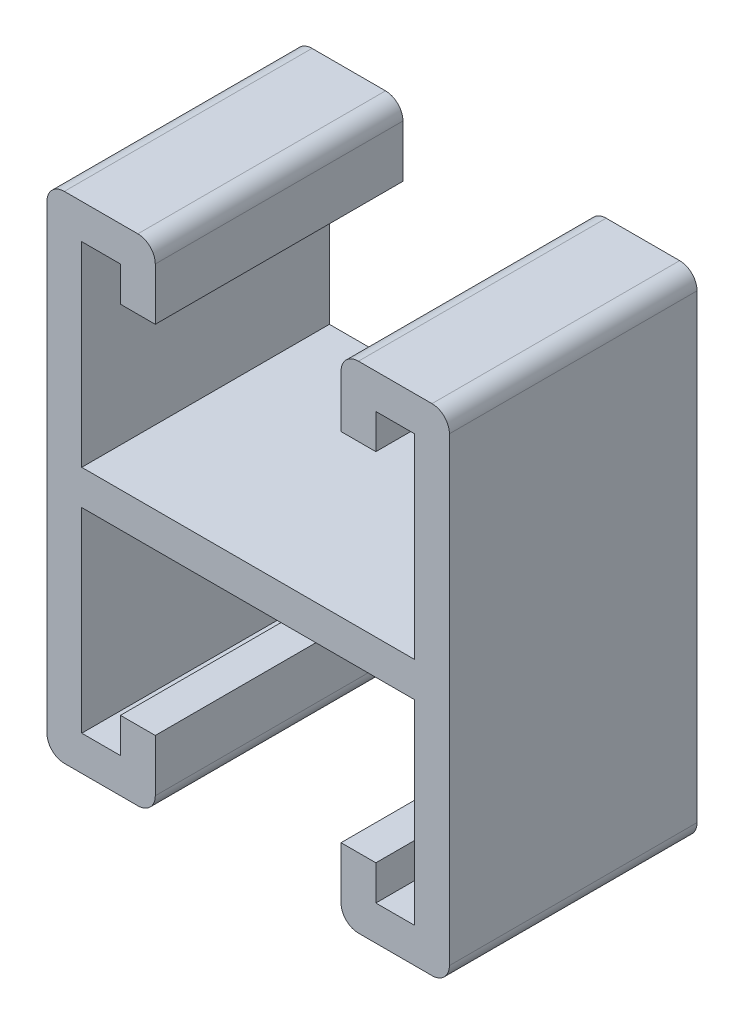
SolidWorks part; units mm, degrees
ref_plane "Plane1" through (0, 0, 0) normal (0, 0, 1) x (1, 0, 0)
ref_plane "Plane2" through (0, 0, 0) normal (0, 1, 0) x (1, 0, 0)
ref_plane "Plane3" through (0, 0, 0) normal (1, 0, 0) x (0, 0, -1)
sketch "Sketch1" plane through (0, 0, 0) normal (0, 0, 1) x (1, 0, 0)
  line L0 (-11.3109, 25.4) -> (-18.8516, 25.4)
  line L1 (-20.6375, 23.6141) -> (-20.6375, -23.6141)
  line L2 (25.727, 0) -> (-25.0678, 0) construction
  line L3 (20.6375, -23.6141) -> (20.6375, 23.6141)
  line L4 (18.8516, 25.4) -> (11.3109, 25.4)
  line L5 (9.525, 23.6141) -> (9.525, 18.2562)
  line L6 (-9.525, 23.6141) -> (-9.525, 18.2562)
  line L7 (-13.0969, 21.8281) -> (-13.0969, 18.2562)
  line L8 (-13.0969, 21.8281) -> (-17.0656, 21.8281)
  line L9 (-17.0656, 21.8281) -> (-17.0656, 1.7859)
  line L10 (-17.0656, 1.7859) -> (17.0656, 1.7859)
  line L11 (17.0656, 1.7859) -> (17.0656, 21.8281)
  line L12 (17.0656, 21.8281) -> (13.0969, 21.8281)
  line L13 (13.0969, 21.8281) -> (13.0969, 18.2562)
  line L14 (-13.0969, 18.2562) -> (-9.525, 18.2562)
  line L15 (9.525, 18.2562) -> (13.0969, 18.2562)
  line L16 (-11.3109, -25.4) -> (-18.8516, -25.4)
  line L17 (-13.0969, -21.8281) -> (-17.0656, -21.8281)
  line L18 (-13.0969, -21.8281) -> (-13.0969, -18.2562)
  line L19 (-9.525, -23.6141) -> (-9.525, -18.2562)
  line L20 (-13.0969, -18.2562) -> (-9.525, -18.2562)
  line L21 (18.8516, -25.4) -> (11.3109, -25.4)
  line L22 (9.525, -23.6141) -> (9.525, -18.2562)
  line L23 (9.525, -18.2562) -> (13.0969, -18.2562)
  line L24 (13.0969, -21.8281) -> (13.0969, -18.2562)
  line L25 (17.0656, -21.8281) -> (13.0969, -21.8281)
  line L26 (17.0656, -1.7859) -> (17.0656, -21.8281)
  line L27 (-17.0656, -21.8281) -> (-17.0656, -1.7859)
  line L28 (-17.0656, -1.7859) -> (17.0656, -1.7859)
  arc A0 (-11.3109, 25.4) -> (-9.525, 23.6141) centre (-11.3109, 23.6141) cw
  arc A1 (-20.6375, 23.6141) -> (-18.8516, 25.4) centre (-18.8516, 23.6141) cw
  arc A2 (-11.3109, -25.4) -> (-9.525, -23.6141) centre (-11.3109, -23.6141) ccw
  arc A3 (-20.6375, -23.6141) -> (-18.8516, -25.4) centre (-18.8516, -23.6141) ccw
  arc A4 (18.8516, 25.4) -> (20.6375, 23.6141) centre (18.8516, 23.6141) cw
  arc A5 (9.525, 23.6141) -> (11.3109, 25.4) centre (11.3109, 23.6141) cw
  arc A6 (18.8516, -25.4) -> (20.6375, -23.6141) centre (18.8516, -23.6141) ccw
  arc A7 (9.525, -23.6141) -> (11.3109, -25.4) centre (11.3109, -23.6141) ccw
  dimension "D2" = 1.7859
  dimension "D3" = 20.6375
  dimension "Width" = 41.275
  dimension "edge" = 11.1125
  dimension "D8" = 19.05
  dimension "ToeHt" = 7.1437
  dimension "D1" = 3.5719
  dimension "D4" = 25.4
  dimension "Height" = 50.8
  dimension "gauge" = 3.5719
extrude "Base-Extrude" add sketch "Sketch1" along normal mid plane 25.4
equation "\"D3@Sketch1\" = \"Width@Sketch1\" / 2"
equation "\"D2@Sketch1\" = \"gauge@Sketch1\" / 2"
equation "\"D8@Sketch1\" = \"Width@Sketch1\" - 2 * \"edge@Sketch1\""
equation "\"gauge@Sketch1\" = \"ToeHt@Sketch1\" / 2"
equation "\"D4@Sketch1\" = \"Height@Sketch1\" / 2"
